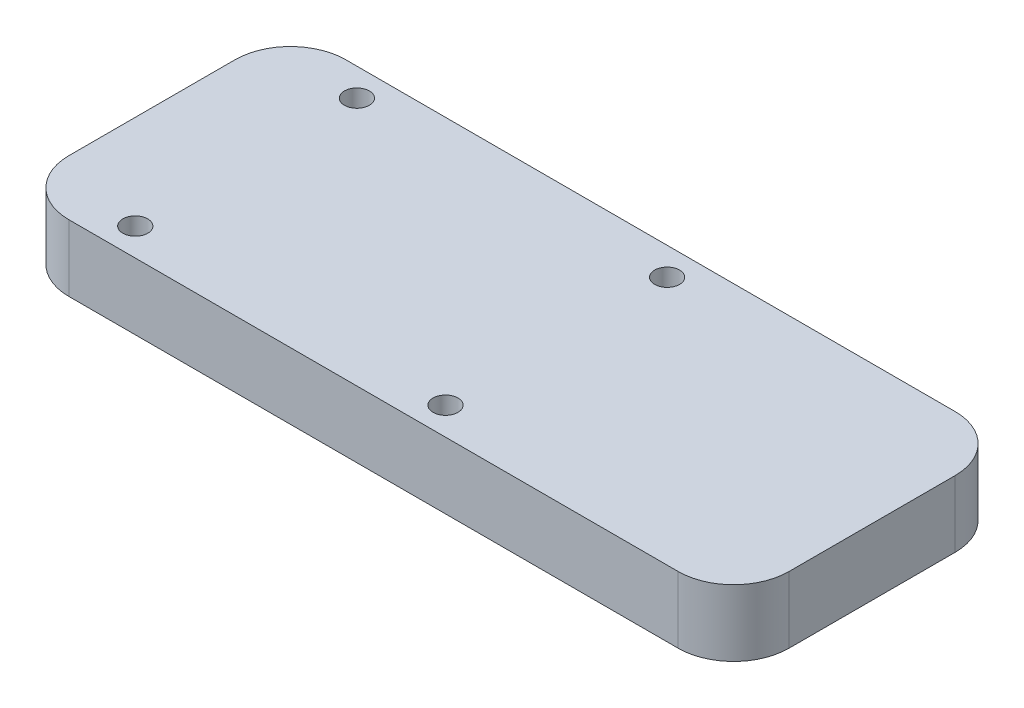
SolidWorks part; units mm, degrees
ref_plane "Alzado" through (0, 0, 0) normal (0, 0, 1) x (1, 0, 0)
ref_plane "Planta" through (0, 0, 0) normal (0, 1, 0) x (1, 0, 0)
ref_plane "Vista lateral" through (0, 0, 0) normal (1, 0, 0) x (0, 0, -1)
sketch "Croquis1" plane through (0, 0, 0) normal (0, 1, 0) x (1, 0, 0)
  line L0 (-92.5828, 33.2119) -> (-92.5828, 3.2119)
  line L1 (-82.5828, -6.7881) -> (27.4172, -6.7881)
  line L2 (37.4172, 3.2119) -> (37.4172, 33.2119)
  line L3 (27.4172, 43.2119) -> (-82.5828, 43.2119)
  circle A0 centre (-19.5828, -1.7881) radius 2.25
  circle A1 centre (-19.5828, 38.2119) radius 2.25
  circle A2 centre (-75.5828, 38.2119) radius 2.25
  circle A3 centre (-75.5828, -1.7881) radius 2.25
  arc A4 (-82.5828, 43.2119) -> (-92.5828, 33.2119) centre (-82.5828, 33.2119) ccw
  arc A5 (-92.5828, 3.2119) -> (-82.5828, -6.7881) centre (-82.5828, 3.2119) ccw
  arc A6 (37.4172, 3.2119) -> (27.4172, -6.7881) centre (27.4172, 3.2119) cw
  arc A7 (37.4172, 33.2119) -> (27.4172, 43.2119) centre (27.4172, 33.2119) ccw
  point P16 (-92.5828, 43.2119)
  dimension "D6" = 4.5
  dimension "D10" = 4.5
  dimension "D11" = 4.5
  dimension "D12" = 10
extrude "Saliente-Extruir1" add sketch "Croquis1" along normal blind 12
